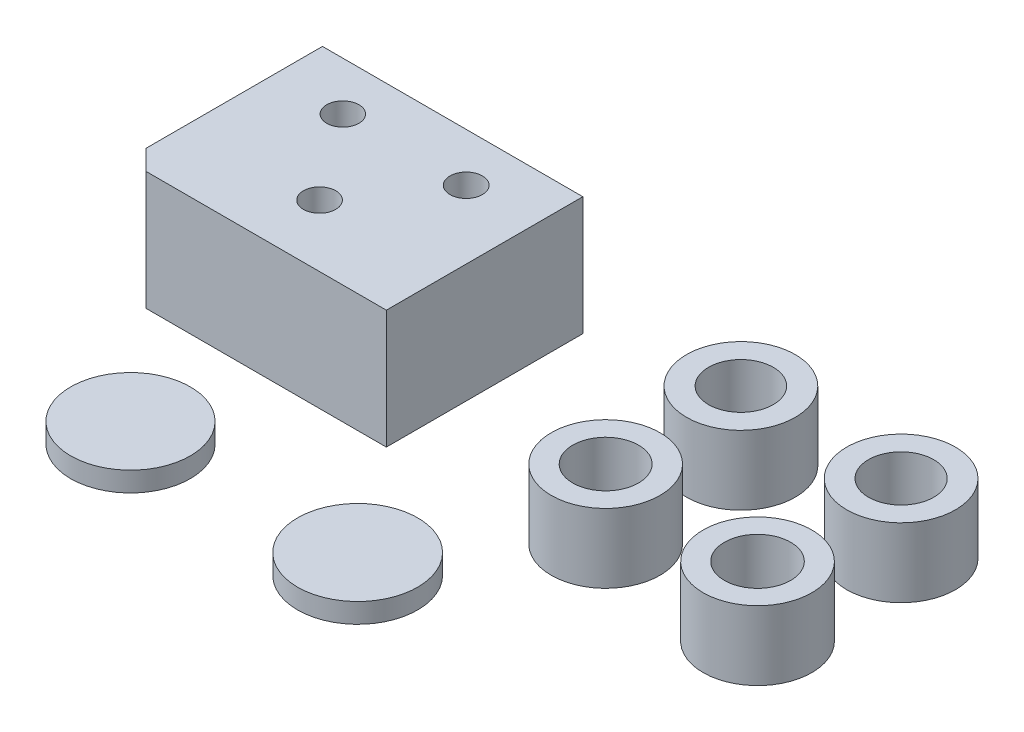
SolidWorks part; units mm, degrees
ref_plane "Front Plane" through (0, 0, 0) normal (0, 0, 1) x (1, 0, 0)
ref_plane "Top Plane" through (0, 0, 0) normal (0, 1, 0) x (1, 0, 0)
ref_plane "Right Plane" through (0, 0, 0) normal (1, 0, 0) x (0, 0, -1)
sketch "Sketch1" plane through (0, 0, 0) normal (0, 1, 0) x (1, 0, 0)
  line L0 (0, 2) -> (2, 0)
  line L1 (2, 0) -> (26.3332, 0)
  line L2 (0, 2) -> (0, 19.8723)
  line L3 (0, 19.8723) -> (26.3332, 19.8723)
  line L4 (26.3332, 0) -> (26.3332, 19.8723)
  circle A0 centre (6.9504, 14.9776) radius 1.63
  circle A1 centre (13.3135, 6.2652) radius 1.635
  circle A2 centre (19.4318, 14.9776) radius 1.64
  point P0 (0, 0)
  point P11 (4.3073, 7.342)
  point P12 (4.5031, 12.2366)
  point P13 (12.2856, 5.3352)
  point P14 (20.3128, 11.6982)
  point P15 (6.8036, 12.2856)
  point P16 (13.2156, 5.0415)
  point P17 (6.9504, 14.9776)
  point P18 (19.4318, 14.9776)
  point P19 (13.3135, 6.2652)
  dimension "D1" = 3.26
  dimension "D2" = 3.27
  dimension "D3" = 3.28
extrude "Boss-Extrude1" add sketch "Sketch1" along normal blind 12
sketch "Sketch2" plane through (0, 0, 0) normal (0, 1, 0) x (1, 0, 0)
  circle A0 centre (45.9049, 16.2901) radius 3.275
  circle A1 centre (62.1088, 16.2901) radius 3.3
  circle A2 centre (45.9049, 2.6085) radius 3.325
  circle A3 centre (62.1088, 1.7678) radius 3.35
  circle A4 centre (45.9049, 16.2901) radius 5.5
  circle A5 centre (62.1088, 16.2901) radius 5.5
  circle A6 centre (45.9049, 2.6085) radius 5.5
  circle A7 centre (62.1088, 1.7678) radius 5.5
  dimension "D1" = 6.55
  dimension "D2" = 6.6
  dimension "D3" = 6.65
  dimension "D4" = 6.7
  dimension "D5" = 11
  dimension "D6" = 11
  dimension "D7" = 11
  dimension "D8" = 11
extrude "Boss-Extrude2" add sketch "Sketch2" along normal blind 7 separate body
sketch "Sketch3" plane through (0, 0, 0) normal (0, 1, 0) x (1, 0, 0)
  circle A0 centre (13.1355, -12.6809) radius 6.05
  circle A1 centre (36.1092, -12.6809) radius 6.075
  dimension "D1" = 12.1
  dimension "D2" = 12.15
extrude "Boss-Extrude3" add sketch "Sketch3" along normal blind 2 separate body
chamfer "Chamfer1" distance 0.5 angle 45 1 edges at (45.9049, 0, 0.7165)
chamfer "Chamfer2" distance 0.5 angle 45 1 edges at (62.1088, 0, 1.5822)
chamfer "Chamfer3" distance 0.5 angle 45 1 edges at (62.1088, 0, -12.9901)
chamfer "Chamfer4" distance 0.5 angle 45 1 edges at (45.9049, 0, -13.0151)
chamfer "Chamfer5" distance 0.5 angle 45 3 edges at (6.9504, 0, -13.3476) (19.4318, 0, -13.3376) (13.3135, 0, -4.6302)
